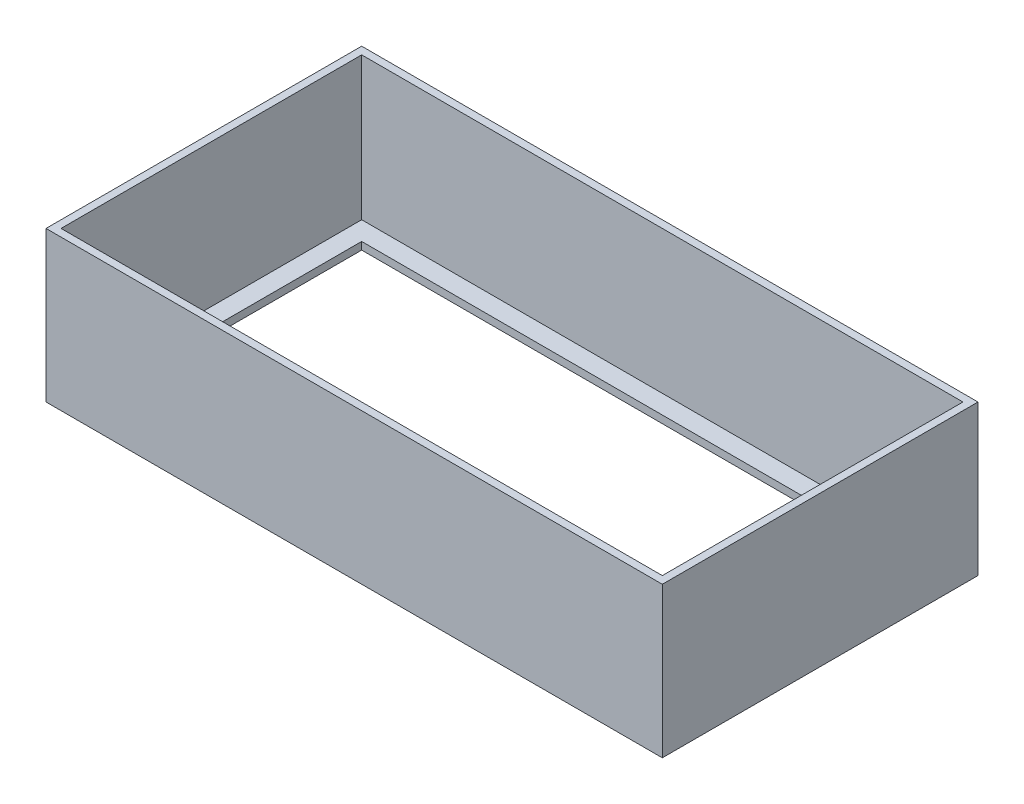
SolidWorks part; units mm, degrees
ref_plane "Front Plane" through (0, 0, 0) normal (0, 0, 1) x (1, 0, 0)
ref_plane "Top Plane" through (0, 0, 0) normal (0, 1, 0) x (1, 0, 0)
ref_plane "Right Plane" through (0, 0, 0) normal (1, 0, 0) x (0, 0, -1)
sketch "Sketch1" plane through (0, 0, 0) normal (0, 1, 0) x (1, 0, 0)
  line L1 (0, 0) -> (164, 0)
  line L2 (0, 0) -> (0, 84)
  line L3 (0, 84) -> (164, 84)
  line L4 (164, 0) -> (164, 84)
  dimension "D1" = 164
  dimension "D2" = 84
extrude "Boss-Extrude1" add sketch "Sketch1" along normal blind 40
shell "Shell1" thickness 2
sketch "Sketch2" plane through (0, 2, 0) normal (0, 1, 0) x (1, 0, 0)
  line L8 (7, 77) -> (7, 7)
  line L9 (7, 7) -> (157, 7)
  line L10 (157, 7) -> (157, 77)
  line L11 (157, 77) -> (7, 77)
  line L12 (7, 77) -> (7, 7)
  line L13 (7, 7) -> (157, 7)
  line L14 (157, 7) -> (157, 77)
  line L15 (157, 77) -> (7, 77)
  dimension "D1" = 5
extrude "Cut-Extrude1" cut sketch "Sketch2" against normal up to surface (2 mm away) up to face at (82, 0, -42)
